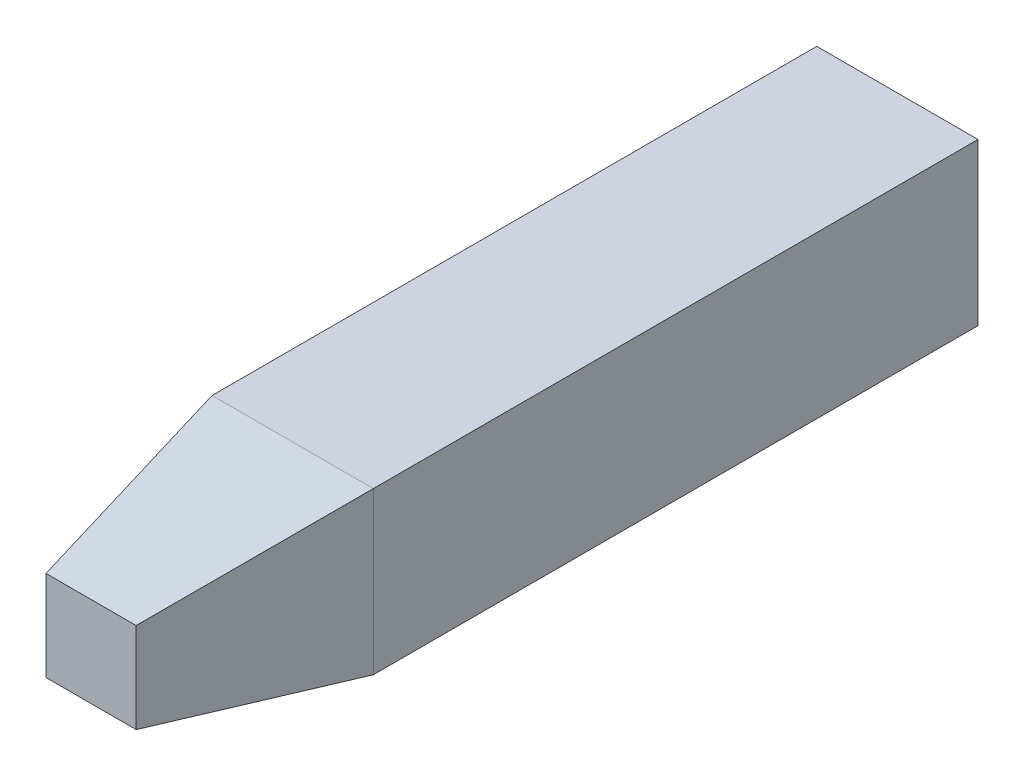
SolidWorks part; units mm, degrees
ref_plane "Front Plane" through (0, 0, 0) normal (0, 0, 1) x (1, 0, 0)
ref_plane "Top Plane" through (0, 0, 0) normal (0, 1, 0) x (1, 0, 0)
ref_plane "Right Plane" through (0, 0, 0) normal (1, 0, 0) x (0, 0, -1)
sketch "Sketch1" plane through (0, 0, 0) normal (0, 0, 1) x (1, 0, 0)
  line L1 (-4, -4) -> (4, -4)
  line L2 (-4, -4) -> (-4, 4)
  line L3 (-4, 4) -> (4, 4)
  line L4 (4, -4) -> (4, 4)
  line L5 (-4, -4) -> (4, 4) construction
  line L6 (-4, 4) -> (4, -4) construction
  point P0 (0, 0)
  dimension "D1" = 8
  dimension "D2" = 8
extrude "Boss-Extrude1" add sketch "Sketch1" along normal blind 30
sketch "Sketch2" plane through (0, 0, 30) normal (0, 0, 1) x (1, 0, 0)
  line L1 (-4, 4) -> (4, 4)
  line L2 (-4, 4) -> (-4, -4)
  line L3 (-4, -4) -> (4, -4)
  line L4 (4, 4) -> (4, -4)
extrude "Boss-Extrude2" add sketch "Sketch2" along normal blind 10 draft 10
